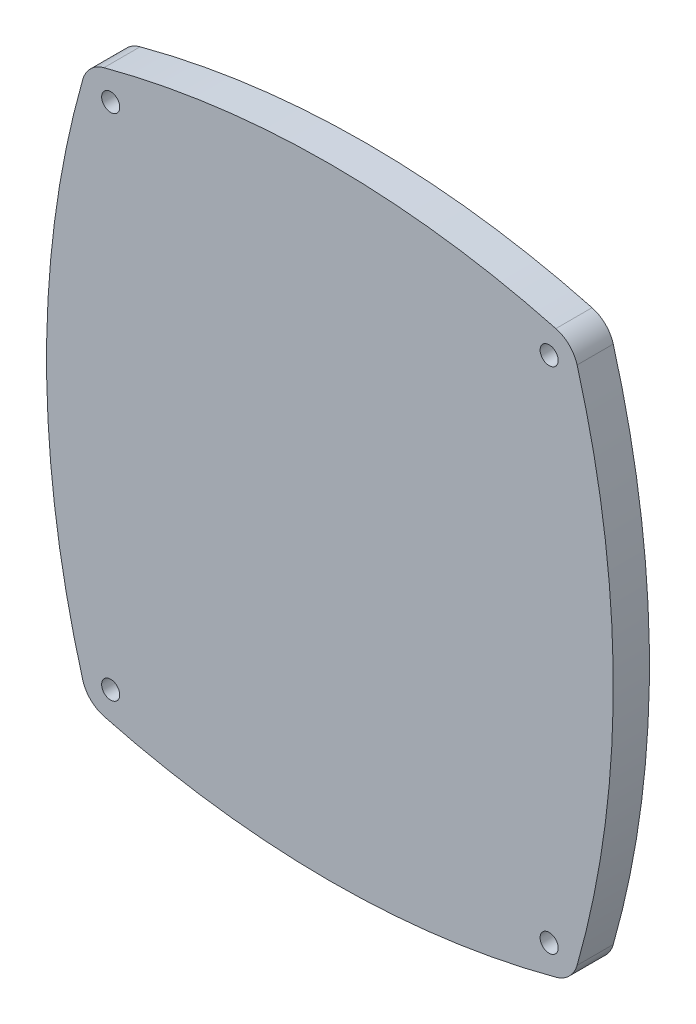
SolidWorks part; units mm, degrees
ref_plane "Front Plane" through (0, 0, 0) normal (0, 0, 1) x (1, 0, 0)
ref_plane "Top Plane" through (0, 0, 0) normal (0, 1, 0) x (1, 0, 0)
ref_plane "Right Plane" through (0, 0, 0) normal (1, 0, 0) x (0, 0, -1)
sketch "Sketch2" plane through (0, 0, 0) normal (0, 0, 1) x (1, 0, 0)
  arc A0 (-54.2482, 36.17) -> (-54.2482, -50.0741) centre (97.7111, -6.952) ccw
  arc A1 (-54.2482, -50.0741) -> (-50.7266, -53.5403) centre (-49.4381, -48.7091) ccw
  arc A2 (-50.7266, -53.5403) -> (24.2302, -53.5403) centre (-13.2482, 86.9896) ccw
  arc A3 (24.2302, -53.5403) -> (27.7518, -50.0741) centre (22.9417, -48.7091) ccw
  arc A4 (27.7518, -50.0741) -> (27.7518, 36.17) centre (-124.2075, -6.952) ccw
  arc A5 (27.7518, 36.17) -> (24.2302, 39.6362) centre (22.9417, 34.8051) ccw
  arc A6 (24.2302, 39.6362) -> (-50.7266, 39.6362) centre (-13.2482, -100.8936) ccw
  arc A7 (-50.7266, 39.6362) -> (-54.2482, 36.17) centre (-49.4381, 34.8051) ccw
extrude "Boss-Extrude1" add sketch "Sketch2" along normal blind 6
sketch "Sketch3" plane through (0, 0, 0) normal (0, 0, -1) x (-1, 0, 0)
  line L0 (27.5573, 1.9731) -> (27.7057, 1.9731)
  line L1 (23.7229, -9.2424) -> (23.7229, -9.4019)
  line L2 (23.7229, -9.4019) -> (29.214, -11.5578)
  line L3 (23.7547, -13.4271) -> (23.7547, -13.5864)
  line L4 (24.0416, -15.7956) -> (24.169, -15.6788)
  line L5 (24.0416, -11.6429) -> (24.169, -11.526)
  line L6 (25.7727, 4.258) -> (25.9214, 4.258)
  line L7 (22.0004, 14.7045) -> (22.013, 14.6954)
  line L8 (13.7054, -27.7067) -> (29.4237, -27.7067)
  spline S0 degree 3 poles (22.4804, 12.9749) (22.2749, 12.8759) (22.1122, 12.7484) (21.9918, 12.5924) knots 15 15 15 15 16 16 16 16
  spline S1 degree 3 poles (23.208, 13.1979) (22.9282, 13.1484) (22.6856, 13.074) (22.4804, 12.9749) knots 14 14 14 14 15 15 15 15
  spline S2 degree 3 poles (25.4063, 13.1184) (24.9568, 13.2208) (24.5266, 13.2721) (24.1159, 13.2721) (23.7903, 13.2721) (23.4877, 13.2476) (23.208, 13.1979) knots 12 12 12 12 13 13 13 14 14 14 14
  spline S3 degree 3 poles (26.6383, 12.7092) (26.2666, 12.8792) (25.8562, 13.0156) (25.4063, 13.1184) knots 11 11 11 11 12 12 12 12
  spline S4 degree 3 poles (27.5624, 12.1145) (27.318, 12.3412) (27.0102, 12.5393) (26.6383, 12.7092) knots 10 10 10 10 11 11 11 11
  spline S5 degree 3 poles (27.7535, 10.7019) (27.8703, 10.9004) (27.9287, 11.1373) (27.9287, 11.4135) (27.9287, 11.6544) (27.8067, 11.8881) (27.5624, 12.1145) knots 8 8 8 8 9 9 9 10 10 10 10
  spline S6 degree 3 poles (27.2861, 10.2241) (27.4809, 10.3445) (27.6366, 10.5038) (27.7535, 10.7019) knots 7 7 7 7 8 8 8 8
  spline S7 degree 3 poles (26.6012, 9.9584) (26.8632, 10.0151) (27.0916, 10.1038) (27.2861, 10.2241) knots 6 6 6 6 7 7 7 7
  spline S8 degree 3 poles (24.4133, 10.0435) (24.8805, 9.9303) (25.3304, 9.8735) (25.7622, 9.8735) (26.0596, 9.8735) (26.3393, 9.9019) (26.6012, 9.9584) knots 4 4 4 4 5 5 5 6 6 6 6
  spline S9 degree 3 poles (23.1334, 10.5109) (23.5195, 10.3126) (23.9459, 10.1569) (24.4133, 10.0435) knots 3 3 3 3 4 4 4 4
  spline S10 degree 3 poles (22.1828, 11.2011) (22.4308, 10.9392) (22.7476, 10.7092) (23.1334, 10.5109) knots 2 2 2 2 3 3 3 3
  spline S11 degree 3 poles (21.9918, 12.5924) (21.8715, 12.4367) (21.8112, 12.2492) (21.8112, 12.0295) (21.8112, 11.7394) (21.935, 11.4633) (22.1828, 11.2011) knots 0 0 0 0 1 1 1 2 2 2 2
  spline S12 degree 3 poles (27.1215, 14.7753) (27.518, 14.6016) (27.8899, 14.389) (28.2368, 14.138) knots 0 0 0 0 1 1 1 1
  spline S13 degree 3 poles (28.2368, 14.138) (28.5837, 13.8866) (28.8848, 13.5998) (29.1395, 13.2776) knots 1 1 1 1 2 2 2 2
  spline S14 degree 3 poles (29.1395, 13.2776) (29.3945, 12.9553) (29.5962, 12.603) (29.745, 12.2207) knots 2 2 2 2 3 3 3 3
  spline S15 degree 3 poles (29.745, 12.2207) (29.8937, 11.8384) (29.968, 11.4314) (29.968, 10.9994) knots 3 3 3 3 4 4 4 4
  spline S16 degree 3 poles (29.968, 10.9994) (29.968, 10.3763) (29.8317, 9.8433) (29.5591, 9.4012) knots 4 4 4 4 5 5 5 5
  spline S17 degree 3 poles (29.5591, 9.4012) (29.2865, 8.9584) (28.9309, 8.5957) (28.4916, 8.3123) knots 5 5 5 5 6 6 6 6
  spline S18 degree 3 poles (28.4916, 8.3123) (28.4303, 8.2726) (28.3652, 8.2381) (28.3014, 8.2015) knots 6 6 6 6 7 7 7 7
  spline S19 degree 3 poles (28.3014, 8.2015) (28.4647, 7.9444) (28.6216, 7.6884) (28.768, 7.4338) knots 7 7 7 7 8 8 8 8
  spline S20 degree 3 poles (28.768, 7.4338) (28.9164, 7.1647) (29.0635, 6.887) (29.2085, 6.6002) knots 8 8 8 8 9 9 9 9
  spline S21 degree 3 poles (29.2085, 6.6002) (29.3539, 6.3135) (29.4831, 6.0248) (29.5962, 5.7344) knots 9 9 9 9 10 10 10 10
  spline S22 degree 3 poles (29.5962, 5.7344) (29.7096, 5.4442) (29.7999, 5.1609) (29.8671, 4.8847) knots 10 10 10 10 11 11 11 11
  spline S23 degree 3 poles (29.8671, 4.8847) (29.9343, 4.6086) (29.968, 4.3503) (29.968, 4.1094) knots 11 11 11 11 12 12 12 12
  spline S24 degree 3 poles (29.968, 4.1094) (29.968, 3.7271) (29.7999, 3.3714) (29.4635, 3.0422) knots 12 12 12 12 13 13 13 13
  spline S25 degree 3 poles (29.4635, 3.0422) (29.1273, 2.713) (28.6759, 2.4262) (28.1093, 2.1819) knots 13 13 13 13 14 14 14 14
  spline S26 degree 3 poles (28.1093, 2.1819) (27.9349, 2.1066) (27.7488, 2.0382) (27.5573, 1.9731) knots 14 14 14 14 15 15 15 15
  spline S27 degree 3 poles (27.7057, 1.9731) (27.9394, 1.7183) (28.1889, 1.4012) (28.4545, 1.0226) knots 16 16 16 16 17 17 17 17
  spline S28 degree 3 poles (28.4545, 1.0226) (28.72, 0.6437) (28.9644, 0.2349) (29.1874, -0.2041) knots 17 17 17 17 18 18 18 18
  spline S29 degree 3 poles (29.1874, -0.2041) (29.4104, -0.6431) (29.5962, -1.0909) (29.745, -1.5477) knots 18 18 18 18 19 19 19 19
  spline S30 degree 3 poles (29.745, -1.5477) (29.8937, -2.0044) (29.968, -2.4381) (29.968, -2.8487) knots 19 19 19 19 20 20 20 20
  spline S31 degree 3 poles (29.968, -2.8487) (29.968, -3.2168) (29.9168, -3.5268) (29.8141, -3.778) knots 20 20 20 20 21 21 21 21
  spline S32 degree 3 poles (29.8141, -3.778) (29.7113, -4.0295) (29.568, -4.233) (29.3838, -4.3888) knots 21 21 21 21 22 22 22 22
  spline S33 degree 3 poles (29.3838, -4.3888) (29.1998, -4.5445) (28.9748, -4.6562) (28.7095, -4.7234) knots 22 22 22 22 23 23 23 23
  spline S34 degree 3 poles (28.7095, -4.7234) (28.6887, -4.7285) (28.6669, -4.7323) (28.6459, -4.7371) knots 23 23 23 23 24 24 24 24
  spline S35 degree 3 poles (28.6459, -4.7371) (28.8556, -4.9943) (29.0532, -5.2605) (29.2298, -5.5411) knots 24 24 24 24 25 25 25 25
  spline S36 degree 3 poles (29.2298, -5.5411) (29.446, -5.8846) (29.6228, -6.2616) (29.7608, -6.6722) knots 25 25 25 25 26 26 26 26
  spline S37 degree 3 poles (29.7608, -6.6722) (29.8989, -7.0829) (29.968, -7.5468) (29.968, -8.0635) knots 26 26 26 26 27 27 27 27
  spline S38 degree 3 poles (29.968, -8.0635) (29.968, -8.3185) (29.8848, -8.5328) (29.7185, -8.7062) knots 27 27 27 27 28 28 28 28
  spline S39 degree 3 poles (29.7185, -8.7062) (29.5522, -8.8797) (29.3202, -9.0194) (29.0228, -9.1256) knots 28 28 28 28 29 29 29 29
  spline S40 degree 3 poles (29.0228, -9.1256) (28.7253, -9.2318) (28.3748, -9.3081) (27.9714, -9.354) knots 29 29 29 29 30 30 30 30
  spline S41 degree 3 poles (27.9714, -9.354) (27.5676, -9.4002) (27.1287, -9.423) (26.6543, -9.423) knots 30 30 30 30 31 31 31 31
  spline S42 degree 3 poles (26.6543, -9.423) (26.2082, -9.423) (25.7355, -9.407) (25.2364, -9.3753) knots 31 31 31 31 32 32 32 32
  spline S43 degree 3 poles (25.2364, -9.3753) (24.7372, -9.3435) (24.2327, -9.2991) (23.7229, -9.2424) knots 32 32 32 32 33 33 33 33
  spline S44 degree 3 poles (29.214, -11.5578) (29.5112, -11.742) (29.7113, -11.9472) (29.8141, -12.1738) knots 35 35 35 35 36 36 36 36
  spline S45 degree 3 poles (29.8141, -12.1738) (29.9168, -12.4005) (29.968, -12.6625) (29.968, -12.9598) knots 36 36 36 36 37 37 37 37
  spline S46 degree 3 poles (29.968, -12.9598) (29.968, -13.1864) (29.9061, -13.367) (29.7821, -13.5014) knots 37 37 37 37 38 38 38 38
  spline S47 degree 3 poles (29.7821, -13.5014) (29.6584, -13.6359) (29.4989, -13.7404) (29.3042, -13.8148) knots 38 38 38 38 39 39 39 39
  spline S48 degree 3 poles (29.3042, -13.8148) (29.1095, -13.8892) (28.8953, -13.9388) (28.6618, -13.9634) knots 39 39 39 39 40 40 40 40
  spline S49 degree 3 poles (28.6618, -13.9634) (28.428, -13.9883) (28.2014, -14.0007) (27.982, -14.0007) knots 40 40 40 40 41 41 41 41
  spline S50 degree 3 poles (27.982, -14.0007) (27.8899, -14.0007) (27.759, -13.9936) (27.5889, -13.9794) knots 41 41 41 41 42 42 42 42
  spline S51 degree 3 poles (27.5889, -13.9794) (27.4191, -13.9651) (27.2243, -13.944) (27.0046, -13.9156) knots 42 42 42 42 43 43 43 43
  spline S52 degree 3 poles (27.0046, -13.9156) (26.7854, -13.8874) (26.5534, -13.8555) (26.3091, -13.8201) knots 43 43 43 43 44 44 44 44
  spline S53 degree 3 poles (26.3091, -13.8201) (26.0648, -13.7845) (25.8225, -13.7493) (25.5816, -13.7139) knots 44 44 44 44 45 45 45 45
  spline S54 degree 3 poles (25.5816, -13.7139) (25.0152, -13.6359) (24.4063, -13.5404) (23.7547, -13.4271) knots 45 45 45 45 46 46 46 46
  spline S55 degree 3 poles (23.7547, -13.5864) (23.8609, -13.6715) (24.0204, -13.7689) (24.2327, -13.8785) knots 47 47 47 47 48 48 48 48
  spline S56 degree 3 poles (24.2327, -13.8785) (24.4451, -13.9883) (24.7568, -14.1423) (25.1675, -14.3406) knots 48 48 48 48 49 49 49 49
  spline S57 degree 3 poles (25.1675, -14.3406) (25.5781, -14.5387) (26.1108, -14.7918) (26.7658, -15.0999) knots 49 49 49 49 50 50 50 50
  spline S58 degree 3 poles (26.7658, -15.0999) (27.4208, -15.408) (28.2405, -15.8063) (29.2245, -16.2948) knots 50 50 50 50 51 51 51 51
  spline S59 degree 3 poles (29.2245, -16.2948) (29.5149, -16.4363) (29.7113, -16.6011) (29.8141, -16.7886) knots 51 51 51 51 52 52 52 52
  spline S60 degree 3 poles (29.8141, -16.7886) (29.9168, -16.9764) (29.968, -17.1833) (29.968, -17.4099) knots 52 52 52 52 53 53 53 53
  spline S61 degree 3 poles (29.968, -17.4099) (29.968, -17.7003) (29.9061, -17.934) (29.7821, -18.1108) knots 53 53 53 53 54 54 54 54
  spline S62 degree 3 poles (29.7821, -18.1108) (29.6584, -18.2878) (29.4919, -18.4242) (29.2829, -18.5198) knots 54 54 54 54 55 55 55 55
  spline S63 degree 3 poles (29.2829, -18.5198) (29.0741, -18.6153) (28.8369, -18.679) (28.5714, -18.711) knots 55 55 55 55 56 56 56 56
  spline S64 degree 3 poles (28.5714, -18.711) (28.3057, -18.7428) (28.0315, -18.7588) (27.7483, -18.7588) knots 56 56 56 56 57 57 57 57
  spline S65 degree 3 poles (27.7483, -18.7588) (27.4579, -18.7588) (27.1146, -18.7411) (26.718, -18.7057) knots 57 57 57 57 58 58 58 58
  spline S66 degree 3 poles (26.718, -18.7057) (26.3215, -18.6703) (25.9039, -18.6242) (25.4647, -18.5675) knots 58 58 58 58 59 59 59 59
  spline S67 degree 3 poles (25.4647, -18.5675) (25.0259, -18.5108) (24.5779, -18.4455) (24.1212, -18.3711) knots 59 59 59 59 60 60 60 60
  spline S68 degree 3 poles (24.1212, -18.3711) (23.6645, -18.2967) (23.2274, -18.2191) (22.8096, -18.1374) knots 60 60 60 60 61 61 61 61
  spline S69 degree 3 poles (22.8096, -18.1374) (22.3918, -18.0562) (22.0095, -17.9728) (21.6625, -17.8878) knots 61 61 61 61 62 62 62 62
  spline S70 degree 3 poles (21.6625, -17.8878) (21.3156, -17.8029) (21.0323, -17.7249) (20.8129, -17.6543) knots 62 62 62 62 63 63 63 63
  spline S71 degree 3 poles (20.8129, -17.6543) (20.5862, -17.5835) (20.4058, -17.5161) (20.2711, -17.4524) knots 63 63 63 63 64 64 64 64
  spline S72 degree 3 poles (20.2711, -17.4524) (20.1367, -17.3886) (20.0322, -17.3163) (19.9578, -17.2347) knots 64 64 64 64 65 65 65 65
  spline S73 degree 3 poles (19.9578, -17.2347) (19.8834, -17.1534) (19.8339, -17.0558) (19.8092, -16.9425) knots 65 65 65 65 66 66 66 66
  spline S74 degree 3 poles (19.8092, -16.9425) (19.7845, -16.8293) (19.7721, -16.6841) (19.7721, -16.5071) knots 66 66 66 66 67 67 67 67
  spline S75 degree 3 poles (19.7721, -16.5071) (19.7721, -16.2381) (19.781, -16.0276) (19.7986, -15.8752) knots 67 67 67 67 68 68 68 68
  spline S76 degree 3 poles (19.7986, -15.8752) (19.8162, -15.7231) (19.8587, -15.6097) (19.9261, -15.5353) knots 68 68 68 68 69 69 69 69
  spline S77 degree 3 poles (19.9261, -15.5353) (19.9934, -15.4611) (20.0907, -15.4169) (20.2182, -15.4026) knots 69 69 69 69 70 70 70 70
  spline S78 degree 3 poles (20.2182, -15.4026) (20.3456, -15.3884) (20.519, -15.3813) (20.7384, -15.3813) knots 70 70 70 70 71 71 71 71
  spline S79 degree 3 poles (20.7384, -15.3813) (20.8589, -15.3813) (20.9969, -15.3866) (21.1527, -15.3973) knots 71 71 71 71 72 72 72 72
  spline S80 degree 3 poles (21.1527, -15.3973) (21.3086, -15.408) (21.4749, -15.4238) (21.6519, -15.4451) knots 72 72 72 72 73 73 73 73
  spline S81 degree 3 poles (21.6519, -15.4451) (21.8289, -15.4664) (22.0113, -15.4894) (22.199, -15.5141) knots 73 73 73 73 74 74 74 74
  spline S82 degree 3 poles (22.199, -15.5141) (22.3866, -15.5389) (22.5687, -15.5655) (22.7457, -15.5937) knots 74 74 74 74 75 75 75 75
  spline S83 degree 3 poles (22.7457, -15.5937) (23.1636, -15.6574) (23.5956, -15.7248) (24.0416, -15.7956) knots 75 75 75 75 76 76 76 76
  spline S84 degree 3 poles (24.169, -15.6788) (24.1479, -15.6645) (24.0133, -15.5884) (23.7654, -15.4504) knots 77 77 77 77 78 78 78 78
  spline S85 degree 3 poles (23.7654, -15.4504) (23.5176, -15.3122) (23.2203, -15.1423) (22.8732, -14.9406) knots 78 78 78 78 79 79 79 79
  spline S86 degree 3 poles (22.8732, -14.9406) (22.5265, -14.7389) (22.1636, -14.521) (21.7845, -14.2873) knots 79 79 79 79 80 80 80 80
  spline S87 degree 3 poles (21.7845, -14.2873) (21.4058, -14.0538) (21.0714, -13.8308) (20.7811, -13.6182) knots 80 80 80 80 81 81 81 81
  spline S88 degree 3 poles (20.7811, -13.6182) (20.4907, -13.4129) (20.2499, -13.1953) (20.0587, -12.9651) knots 81 81 81 81 82 82 82 82
  spline S89 degree 3 poles (20.0587, -12.9651) (19.8676, -12.735) (19.7721, -12.4606) (19.7721, -12.142) knots 82 82 82 82 83 83 83 83
  spline S90 degree 3 poles (19.7721, -12.142) (19.7721, -11.8446) (19.8587, -11.5896) (20.0322, -11.3772) knots 83 83 83 83 84 84 84 84
  spline S91 degree 3 poles (20.0322, -11.3772) (20.2058, -11.1649) (20.4518, -11.0586) (20.7704, -11.0586) knots 84 84 84 84 85 85 85 85
  spline S92 degree 3 poles (20.7704, -11.0586) (21.0464, -11.0586) (21.3086, -11.0764) (21.5563, -11.1117) knots 85 85 85 85 86 86 86 86
  spline S93 degree 3 poles (21.5563, -11.1117) (21.8041, -11.1473) (22.0448, -11.1915) (22.2785, -11.2446) knots 86 86 86 86 87 87 87 87
  spline S94 degree 3 poles (22.2785, -11.2446) (22.512, -11.2977) (22.7406, -11.3525) (22.9636, -11.4092) knots 87 87 87 87 88 88 88 88
  spline S95 degree 3 poles (22.9636, -11.4092) (23.1866, -11.4659) (23.4148, -11.519) (23.6485, -11.5685) knots 88 88 88 88 89 89 89 89
  spline S96 degree 3 poles (23.6485, -11.5685) (23.8114, -11.6039) (23.9141, -11.6252) (23.9566, -11.6322) knots 89 89 89 89 90 90 90 90
  spline S97 degree 3 poles (23.9566, -11.6322) (23.9991, -11.6393) (24.0276, -11.6429) (24.0416, -11.6429) knots 90 90 90 90 91 91 91 91
  spline S98 degree 3 poles (24.169, -11.526) (24.1479, -11.5118) (24.015, -11.4303) (23.7709, -11.2817) knots 92 92 92 92 93 93 93 93
  spline S99 degree 3 poles (23.7709, -11.2817) (23.5265, -11.1331) (23.231, -10.9508) (22.8839, -10.7348) knots 93 93 93 93 94 94 94 94
  spline S100 degree 3 poles (22.8839, -10.7348) (22.5371, -10.519) (22.1722, -10.2887) (21.79, -10.0443) knots 94 94 94 94 95 95 95 95
  spline S101 degree 3 poles (21.79, -10.0443) (21.4075, -9.8) (21.0714, -9.5716) (20.7811, -9.3593) knots 95 95 95 95 96 96 96 96
  spline S102 degree 3 poles (20.7811, -9.3593) (20.4979, -9.154) (20.2589, -8.9488) (20.0642, -8.7433) knots 96 96 96 96 97 97 97 97
  spline S103 degree 3 poles (20.0642, -8.7433) (19.8693, -8.5379) (19.7721, -8.2866) (19.7721, -7.9893) knots 97 97 97 97 98 98 98 98
  spline S104 degree 3 poles (19.7721, -7.9893) (19.7721, -7.6565) (19.8587, -7.3752) (20.0322, -7.1449) knots 98 98 98 98 99 99 99 99
  spline S105 degree 3 poles (20.0322, -7.1449) (20.2058, -6.9149) (20.4518, -6.7997) (20.7704, -6.7997) knots 99 99 99 99 100 100 100 100
  spline S106 degree 3 poles (20.7704, -6.7997) (21.2589, -6.7997) (21.7227, -6.8245) (22.1617, -6.874) knots 100 100 100 100 101 101 101 101
  spline S107 degree 3 poles (22.1617, -6.874) (22.6007, -6.9234) (23.0327, -6.9803) (23.4574, -7.0441) knots 101 101 101 101 102 102 102 102
  spline S108 degree 3 poles (23.4574, -7.0441) (23.8822, -7.1077) (24.3125, -7.1643) (24.7479, -7.2138) knots 102 102 102 102 103 103 103 103
  spline S109 degree 3 poles (24.7479, -7.2138) (25.1833, -7.2633) (25.6453, -7.2883) (26.1338, -7.2883) knots 103 103 103 103 104 104 104 104
  spline S110 degree 3 poles (26.1338, -7.2883) (26.5163, -7.2883) (26.8279, -7.2388) (27.0686, -7.1396) knots 104 104 104 104 105 105 105 105
  spline S111 degree 3 poles (27.0686, -7.1396) (27.3093, -7.0403) (27.4296, -6.9202) (27.4296, -6.7784) knots 105 105 105 105 106 106 106 106
  spline S112 degree 3 poles (27.4296, -6.7784) (27.4296, -6.6298) (27.3978, -6.4741) (27.3341, -6.3111) knots 106 106 106 106 107 107 107 107
  spline S113 degree 3 poles (27.3341, -6.3111) (27.2703, -6.1482) (27.1888, -5.9818) (27.0897, -5.8119) knots 107 107 107 107 108 108 108 108
  spline S114 degree 3 poles (27.0897, -5.8119) (26.9905, -5.642) (26.8756, -5.4756) (26.7445, -5.3127) knots 108 108 108 108 109 109 109 109
  spline S115 degree 3 poles (26.7445, -5.3127) (26.6136, -5.1499) (26.4773, -4.9941) (26.3355, -4.8456) knots 109 109 109 109 110 110 110 110
  spline S116 degree 3 poles (26.3355, -4.8456) (26.2725, -4.7784) (26.2063, -4.7113) (26.14, -4.6443) knots 110 110 110 110 111 111 111 111
  spline S117 degree 3 poles (26.14, -4.6443) (25.5909, -4.5462) (25.0255, -4.4306) (24.44, -4.2931) knots 111 111 111 111 112 112 112 112
  spline S118 degree 3 poles (24.44, -4.2931) (23.8062, -4.1445) (23.1743, -3.9871) (22.544, -3.8206) knots 112 112 112 112 113 113 113 113
  spline S119 degree 3 poles (22.544, -3.8206) (21.9139, -3.6543) (21.3333, -3.5072) (20.8022, -3.3799) knots 113 113 113 113 114 114 114 114
  spline S120 degree 3 poles (20.8022, -3.3799) (20.6182, -3.3304) (20.4608, -3.231) (20.3295, -3.0824) knots 114 114 114 114 115 115 115 115
  spline S121 degree 3 poles (20.3295, -3.0824) (20.1986, -2.9338) (20.0924, -2.7658) (20.0109, -2.5779) knots 115 115 115 115 116 116 116 116
  spline S122 degree 3 poles (20.0109, -2.5779) (19.9295, -2.3903) (19.8693, -2.1956) (19.8305, -1.9937) knots 116 116 116 116 117 117 117 117
  spline S123 degree 3 poles (19.8305, -1.9937) (19.7915, -1.792) (19.7721, -1.6097) (19.7721, -1.4468) knots 117 117 117 117 118 118 118 118
  spline S124 degree 3 poles (19.7721, -1.4468) (19.7721, -1.1493) (19.8269, -0.9476) (19.9367, -0.8415) knots 118 118 118 118 119 119 119 119
  spline S125 degree 3 poles (19.9367, -0.8415) (20.0463, -0.7352) (20.1934, -0.6822) (20.3773, -0.6822) knots 119 119 119 119 120 120 120 120
  spline S126 degree 3 poles (20.3773, -0.6822) (20.5333, -0.6822) (20.758, -0.7175) (21.0519, -0.7884) knots 120 120 120 120 121 121 121 121
  spline S127 degree 3 poles (21.0519, -0.7884) (21.3457, -0.859) (21.6784, -0.9476) (22.0502, -1.0538) knots 121 121 121 121 122 122 122 122
  spline S128 degree 3 poles (22.0502, -1.0538) (22.422, -1.16) (22.822, -1.2733) (23.2502, -1.3937) knots 122 122 122 122 123 123 123 123
  spline S129 degree 3 poles (23.2502, -1.3937) (23.6787, -1.5141) (24.1071, -1.6274) (24.5355, -1.7336) knots 123 123 123 123 124 124 124 124
  spline S130 degree 3 poles (24.5355, -1.7336) (24.9639, -1.8398) (25.3816, -1.9284) (25.7888, -1.999) knots 124 124 124 124 125 125 125 125
  spline S131 degree 3 poles (25.7888, -1.999) (26.1959, -2.0699) (26.5623, -2.1052) (26.888, -2.1052) knots 125 125 125 125 126 126 126 126
  spline S132 degree 3 poles (26.888, -2.1052) (27.2066, -2.1052) (27.4596, -2.0699) (27.6473, -1.999) knots 126 126 126 126 127 127 127 127
  spline S133 degree 3 poles (27.6473, -1.999) (27.8349, -1.9284) (27.9287, -1.7831) (27.9287, -1.5636) knots 127 127 127 127 128 128 128 128
  spline S134 degree 3 poles (27.9287, -1.5636) (27.9287, -1.3088) (27.8404, -1.0256) (27.6633, -0.714) knots 128 128 128 128 129 129 129 129
  spline S135 degree 3 poles (27.6633, -0.714) (27.4865, -0.4022) (27.272, -0.0873) (27.0208, 0.2313) knots 129 129 129 129 130 130 130 130
  spline S136 degree 3 poles (27.0208, 0.2313) (26.7694, 0.5498) (26.5091, 0.8616) (26.24, 1.1659) knots 130 130 130 130 131 131 131 131
  spline S137 degree 3 poles (26.24, 1.1659) (26.1144, 1.3081) (25.9981, 1.4418) (25.8895, 1.5686) knots 131 131 131 131 132 132 132 132
  spline S138 degree 3 poles (25.8895, 1.5686) (25.2173, 1.4592) (24.5176, 1.4011) (23.7867, 1.4011) knots 132 132 132 132 133 133 133 133
  spline S139 degree 3 poles (23.7867, 1.4011) (23.1564, 1.4011) (22.4715, 1.4471) (21.7316, 1.5391) knots 133 133 133 133 134 134 134 134
  spline S140 degree 3 poles (21.7316, 1.5391) (20.9917, 1.6313) (20.2288, 1.7659) (19.4429, 1.9427) knots 134 134 134 134 135 135 135 135
  spline S141 degree 3 poles (19.4429, 1.9427) (18.6569, 2.1198) (17.8674, 2.3307) (17.0744, 2.5748) knots 135 135 135 135 136 136 136 136
  spline S142 degree 3 poles (17.0744, 2.5748) (16.2812, 2.8192) (15.52, 3.0953) (14.7908, 3.4034) knots 136 136 136 136 137 137 137 137
  spline S143 degree 3 poles (14.7908, 3.4034) (14.0616, 3.7113) (13.38, 4.0457) (12.7463, 4.4069) knots 137 137 137 137 138 138 138 138
  spline S144 degree 3 poles (12.7463, 4.4069) (12.1127, 4.7679) (11.5604, 5.1467) (11.0895, 5.5432) knots 138 138 138 138 139 139 139 139
  spline S145 degree 3 poles (11.0895, 5.5432) (10.6187, 5.9398) (10.2487, 6.354) (9.9795, 6.7858) knots 139 139 139 139 140 140 140 140
  spline S146 degree 3 poles (9.9795, 6.7858) (9.7105, 7.218) (9.576, 7.6568) (9.576, 8.1029) knots 140 140 140 140 141 141 141 141
  spline S147 degree 3 poles (9.576, 8.1029) (9.576, 8.4073) (9.645, 8.6587) (9.783, 8.8569) knots 141 141 141 141 142 142 142 142
  spline S148 degree 3 poles (9.783, 8.8569) (9.9211, 9.0553) (10.1035, 9.211) (10.3301, 9.3242) knots 142 142 142 142 143 143 143 143
  spline S149 degree 3 poles (10.3301, 9.3242) (10.5567, 9.4376) (10.8133, 9.517) (11.1001, 9.5634) knots 143 143 143 143 144 144 144 144
  spline S150 degree 3 poles (11.1001, 9.5634) (11.3868, 9.6093) (11.6789, 9.6321) (11.9763, 9.6321) knots 144 144 144 144 145 145 145 145
  spline S151 degree 3 poles (11.9763, 9.6321) (12.6419, 9.6321) (13.3199, 9.5562) (14.0102, 9.4041) knots 145 145 145 145 146 146 146 146
  spline S152 degree 3 poles (14.0102, 9.4041) (14.7004, 9.2516) (15.3946, 9.0464) (16.0919, 8.7881) knots 146 146 146 146 147 147 147 147
  spline S153 degree 3 poles (16.0919, 8.7881) (16.7893, 8.5294) (17.4885, 8.2302) (18.1895, 7.8905) knots 147 147 147 147 148 148 148 148
  spline S154 degree 3 poles (18.1895, 7.8905) (18.8904, 7.5506) (19.5862, 7.1966) (20.2766, 6.8283) knots 148 148 148 148 149 149 149 149
  spline S155 degree 3 poles (20.2766, 6.8283) (20.9668, 6.4602) (21.6466, 6.0904) (22.3157, 5.7186) knots 149 149 149 149 150 150 150 150
  spline S156 degree 3 poles (22.3157, 5.7186) (22.9849, 5.3469) (23.6379, 4.9981) (24.2754, 4.6723) knots 150 150 150 150 151 151 151 151
  spline S157 degree 3 poles (24.2754, 4.6723) (24.3461, 4.6371) (24.4382, 4.5996) (24.5513, 4.561) knots 151 151 151 151 152 152 152 152
  spline S158 degree 3 poles (24.5513, 4.561) (24.6647, 4.522) (24.7867, 4.4847) (24.9178, 4.4493) knots 152 152 152 152 153 153 153 153
  spline S159 degree 3 poles (24.9178, 4.4493) (25.0489, 4.4141) (25.1886, 4.3785) (25.3373, 4.3431) knots 153 153 153 153 154 154 154 154
  spline S160 degree 3 poles (25.3373, 4.3431) (25.486, 4.3077) (25.6311, 4.2794) (25.7727, 4.258) knots 154 154 154 154 155 155 155 155
  spline S161 degree 3 poles (25.9214, 4.258) (26.1056, 4.258) (26.2844, 4.2776) (26.4579, 4.3166) knots 156 156 156 156 157 157 157 157
  spline S162 degree 3 poles (26.4579, 4.3166) (26.6314, 4.3553) (26.7871, 4.4034) (26.9251, 4.4598) knots 157 157 157 157 158 158 158 158
  spline S163 degree 3 poles (26.9251, 4.4598) (27.0631, 4.5167) (27.173, 4.5766) (27.2545, 4.6404) knots 158 158 158 158 159 159 159 159
  spline S164 degree 3 poles (27.2545, 4.6404) (27.3359, 4.7041) (27.3765, 4.7644) (27.3765, 4.821) knots 159 159 159 159 160 160 160 160
  spline S165 degree 3 poles (27.3765, 4.821) (27.3765, 4.9557) (27.3483, 5.1094) (27.2916, 5.2832) knots 160 160 160 160 161 161 161 161
  spline S166 degree 3 poles (27.2916, 5.2832) (27.2349, 5.4566) (27.1588, 5.6404) (27.0631, 5.8355) knots 161 161 161 161 162 162 162 162
  spline S167 degree 3 poles (27.0631, 5.8355) (26.9675, 6.0301) (26.8579, 6.2301) (26.7338, 6.4353) knots 162 162 162 162 163 163 163 163
  spline S168 degree 3 poles (26.7338, 6.4353) (26.6102, 6.6408) (26.4844, 6.8389) (26.3569, 7.0301) knots 163 163 163 163 164 164 164 164
  spline S169 degree 3 poles (26.3569, 7.0301) (26.2481, 7.1934) (26.1309, 7.3606) (26.0098, 7.5295) knots 164 164 164 164 165 165 165 165
  spline S170 degree 3 poles (26.0098, 7.5295) (25.7831, 7.508) (25.5556, 7.4944) (25.3266, 7.4944) knots 165 165 165 165 166 166 166 166
  spline S171 degree 3 poles (25.3266, 7.4944) (24.5479, 7.4944) (23.8204, 7.6113) (23.144, 7.845) knots 166 166 166 166 167 167 167 167
  spline S172 degree 3 poles (23.144, 7.845) (22.468, 8.0787) (21.8802, 8.4134) (21.3811, 8.8488) knots 167 167 167 167 168 168 168 168
  spline S173 degree 3 poles (21.3811, 8.8488) (20.8818, 9.2844) (20.4889, 9.817) (20.2022, 10.4471) knots 168 168 168 168 169 169 169 169
  spline S174 degree 3 poles (20.2022, 10.4471) (20.0185, 10.8509) (19.8943, 11.287) (19.8283, 11.7547) knots 169 169 169 169 170 170 170 170
  spline S175 degree 3 poles (19.8283, 11.7547) (20.0419, 12.9788) (20.8529, 14.0362) (22.0004, 14.7045) knots 170 170 170 170 171 171 171 171
  spline S176 degree 3 poles (22.013, 14.6954) (22.1416, 14.7598) (22.2736, 14.8172) (22.4066, 14.8715) knots 172 172 172 172 173 173 173 173
  spline S177 degree 3 poles (22.4066, 14.8715) (18.4339, 14.8715) (14.165, 14.8715) (13.7054, 14.8715) knots 173 173 173 173 174 174 174 174
  spline S178 degree 3 poles (13.7054, 14.8715) (12.8254, 14.8715) (11.51, 14.2849) (10.5198, 13.2946) knots 174 174 174 174 175 175 175 175
  spline S179 degree 3 poles (10.5198, 13.2946) (9.5297, 12.3044) (-4.0325, -2.6431) (-5.1636, -4.1484) knots 175 175 175 175 176 176 176 176
  spline S180 degree 3 poles (-5.1636, -4.1484) (-6.2948, -5.6538) (-6.2613, -7.0563) (-5.1636, -8.7598) knots 176 176 176 176 177 177 177 177
  spline S181 degree 3 poles (-5.1636, -8.7598) (-4.066, -10.4633) (9.3874, -25.1688) (10.5198, -26.203) knots 177 177 177 177 178 178 178 178
  spline S182 degree 3 poles (10.5198, -26.203) (11.6523, -27.2373) (13.0288, -27.7067) (13.7054, -27.7067) knots 178 178 178 178 179 179 179 179
  spline S183 degree 3 poles (29.4237, -27.7067) (31.1242, -27.7067) (31.7763, -26.6245) (32.0629, -25.0674) knots 180 180 180 180 181 181 181 181
  spline S184 degree 3 poles (32.0629, -25.0674) (32.8839, -20.6097) (32.5908, -17.2079) (32.5908, -7.6479) knots 181 181 181 181 182 182 182 182
  spline S185 degree 3 poles (32.5908, -7.6479) (32.5908, 1.9121) (32.7664, 7.4252) (32.0629, 12.2323) knots 182 182 182 182 183 183 183 183
  spline S186 degree 3 poles (32.0629, 12.2323) (31.8165, 13.9175) (30.8309, 14.8715) (29.4237, 14.8715) knots 183 183 183 183 184 184 184 184
  spline S187 degree 2 poles (29.4237, 14.8715) (28.4045, 14.8715) (26.8857, 14.8715) knots 184 184 184 185 185 185
  spline S188 degree 3 poles (26.8857, 14.8715) (26.9648, 14.8406) (27.0437, 14.8093) (27.1215, 14.7753) knots 185 185 185 185 186 186 186 186
  spline S189 degree 3 poles (17.961, -2.3283) (17.6674, -2.6257) (17.2761, -2.7743) (16.7874, -2.7743) (16.6247, -2.7743) (16.4407, -2.7389) (16.2352, -2.6681) knots 12 12 12 12 13 13 13 14 14 14 14
  spline S190 degree 3 poles (18.2373, -0.0184) (18.3471, -0.2768) (18.402, -0.5865) (18.402, -0.9476) (18.402, -1.5707) (18.255, -2.031) (17.961, -2.3283) knots 10 10 10 10 11 11 11 12 12 12 12
  spline S191 degree 3 poles (17.8071, 0.6242) (17.9842, 0.4543) (18.1277, 0.24) (18.2373, -0.0184) knots 9 9 9 9 10 10 10 10
  spline S192 degree 3 poles (17.2017, 0.9961) (17.4284, 0.9181) (17.6301, 0.7942) (17.8071, 0.6242) knots 8 8 8 8 9 9 9 9
  spline S193 degree 3 poles (15.8211, 0.9694) (16.0121, 1.065) (16.239, 1.1128) (16.5008, 1.1128) (16.7416, 1.1128) (16.9751, 1.0739) (17.2017, 0.9961) knots 6 6 6 6 7 7 7 8 8 8 8
  spline S194 degree 3 poles (15.0987, 0.0082) (15.1554, 0.2276) (15.2422, 0.4189) (15.359, 0.5818) (15.4759, 0.7447) (15.6298, 0.8739) (15.8211, 0.9694) knots 4 4 4 4 5 5 5 6 6 6 6
  spline S195 degree 3 poles (15.1998, -1.6858) (15.0759, -1.4202) (15.0138, -1.0892) (15.0138, -0.6926) (15.0138, -0.4449) (15.0422, -0.2112) (15.0987, 0.0082) knots 2 2 2 2 3 3 3 4 4 4 4
  spline S196 degree 3 poles (15.6565, -2.3229) (15.4759, -2.1636) (15.3236, -1.9513) (15.1998, -1.6858) knots 1 1 1 1 2 2 2 2
  spline S197 degree 3 poles (16.2352, -2.6681) (16.03, -2.5975) (15.8369, -2.4824) (15.6565, -2.3229) knots 0 0 0 0 1 1 1 1
  spline S198 degree 3 poles (19.5595, 5.1346) (18.8516, 5.4918) (18.1222, 5.83) (17.3716, 6.1485) knots 11 11 11 11 12 12 12 12
  spline S199 degree 3 poles (21.4713, 4.1199) (20.9049, 4.4387) (20.2677, 4.7768) (19.5595, 5.1346) knots 10 10 10 10 11 11 11 11
  spline S200 degree 3 poles (19.3738, 4.2687) (20.0924, 4.1698) (20.7917, 4.1199) (21.4713, 4.1199) knots 9 9 9 9 10 10 10 10
  spline S201 degree 3 poles (17.2761, 4.6723) (17.9559, 4.5024) (18.6552, 4.3679) (19.3738, 4.2687) knots 8 8 8 8 9 9 9 9
  spline S202 degree 3 poles (15.3537, 5.2514) (15.9556, 5.0351) (16.5964, 4.8423) (17.2761, 4.6723) knots 7 7 7 7 8 8 8 8
  spline S203 degree 3 poles (13.7712, 5.9312) (14.2245, 5.6935) (14.752, 5.4672) (15.3537, 5.2514) knots 6 6 6 6 7 7 7 7
  spline S204 degree 3 poles (12.6932, 6.6427) (12.9587, 6.4052) (13.3182, 6.1681) (13.7712, 5.9312) knots 5 5 5 5 6 6 6 6
  spline S205 degree 3 poles (12.5126, 7.4073) (12.3676, 7.3967) (12.2949, 7.363) (12.2949, 7.3063) (12.2949, 7.1011) (12.4277, 6.8798) (12.6932, 6.6427) knots 3 3 3 3 4 4 4 5 5 5 5
  spline S206 degree 3 poles (13.0384, 7.4231) (12.8331, 7.4231) (12.6578, 7.418) (12.5126, 7.4073) knots 2 2 2 2 3 3 3 3
  spline S207 degree 3 poles (15.1254, 6.9771) (14.3784, 7.2107) (13.6829, 7.3594) (13.0384, 7.4231) knots 1 1 1 1 2 2 2 2
  spline S208 degree 3 poles (17.3716, 6.1485) (16.6211, 6.4673) (15.8725, 6.7434) (15.1254, 6.9771) knots 0 0 0 0 1 1 1 1
extrude "Cut-Extrude1" cut sketch "Sketch3" against normal blind 3
hole_wizard "CBORE for 1/4 Binding Head Machine Screw1" positions "Sketch5" profile "Sketch4" counterbore size "1/4" standard "ANSI Inch" end condition through all
sketch "Sketch5" plane through (0, 0, 0) normal (0, 0, -1) x (-1, 0, 0)
  point P0 (49.6128, -49.1573)
  point P3 (-23.1164, -49.1573)
  point P6 (-23.1164, 35.2532)
  point P9 (49.6128, 35.2532)
sketch "Sketch4" plane through (-49.6128, -49.1573, 0) normal (1, 0, 0) x (0, 1, 0)
  line L0 (0, 0) -> (0, 6)
  line L1 (0, 6) -> (1.5, 6)
  line L3 (1.5, 6) -> (1.5, 2.5)
  line L4 (1.5, 2.5) -> (3, 2.5)
  line L5 (3, 2.5) -> (3, 0)
  line L7 (3, 0) -> (0, 0)
  line L11 (0, -6.35) -> (0, 107.95) construction
  dimension "Thru Hole Dia." = 3
  dimension "Thru Hole Depth" = 6
  dimension "C'Bore Dia." = 6
  dimension "C'Bore Depth" = 2.5
